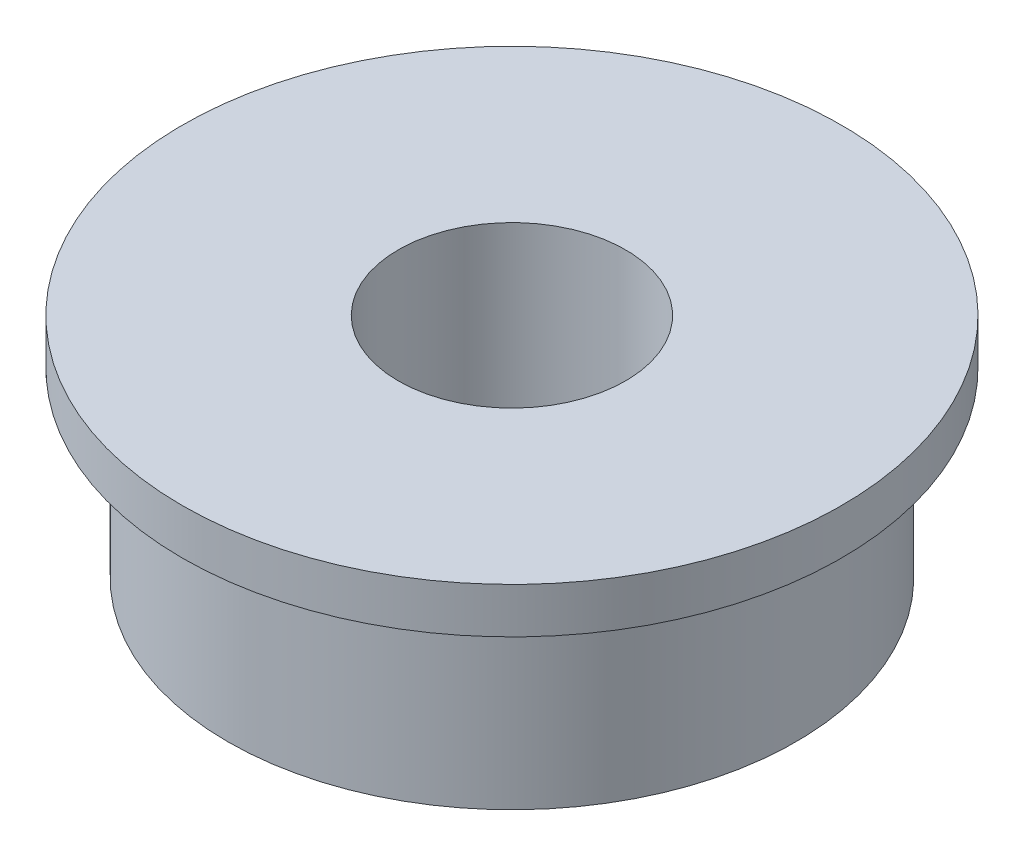
SolidWorks part; units mm, degrees
material "铸造不锈钢"
ref_plane "前视基准面" through (0, 0, 0) normal (0, 0, 1) x (1, 0, 0)
ref_plane "上视基准面" through (0, 0, 0) normal (0, 1, 0) x (1, 0, 0)
ref_plane "右视基准面" through (0, 0, 0) normal (1, 0, 0) x (0, 0, -1)
other "Configuration Table"
sketch "草图1" plane through (0, 0, 0) normal (0, 1, 0) x (1, 0, 0)
  circle A0 centre (0, 0) radius 2
  circle A1 centre (0, 0) radius 5
  dimension "D1" = 10
  dimension "D2" = 4
extrude "凸台-拉伸1" add sketch "草图1" along normal blind 3.2
sketch "草图2" plane through (0, 3.2, 0) normal (0, 1, 0) x (1, 0, 0)
  circle A0 centre (0, 0) radius 2
  circle A1 centre (0, 0) radius 5.8
  dimension "D1" = 4
  dimension "D2" = 11.6
extrude "凸台-拉伸2" add sketch "草图2" along normal blind 0.8
